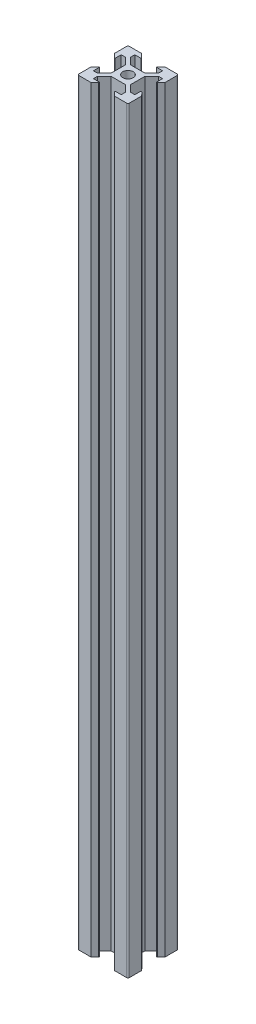
SolidWorks part; units mm, degrees
ref_plane "Front Plane" through (0, 0, 0) normal (0, 0, 1) x (1, 0, 0)
ref_plane "Top Plane" through (0, 0, 0) normal (0, 1, 0) x (1, 0, 0)
ref_plane "Right Plane" through (0, 0, 0) normal (1, 0, 0) x (0, 0, -1)
sketch "Sketch1" plane through (0, 0, 0) normal (0, 1, 0) x (1, 0, 0)
  line L0 (-2.1465, 12.2219) -> (22.938, 12.2219) construction
  line L1 (7.155, 13.9) -> (4.5, 16.555)
  line L2 (0.5, 0) -> (5.42, 0)
  line L3 (0, 0.5) -> (0, 5.42)
  line L4 (0.5, 20) -> (5.42, 20)
  line L5 (20, 0.5) -> (20, 19.5)
  line L6 (7.155, 13.9) -> (12.8341, 13.9)
  line L7 (6.1, 12.845) -> (6.1, 7.1491)
  line L8 (7.1445, 6.1) -> (12.8546, 6.1)
  line L9 (13.9, 12.8445) -> (13.9, 7.1491)
  line L10 (0, 20) -> (4.5, 20)
  line L11 (0, 20) -> (0, 15.5)
  line L12 (1.8, 15.5) -> (3.445, 15.5)
  line L13 (4.5, 18.2) -> (4.5, 16.555)
  line L14 (6.1, 12.845) -> (6.0943, 12.8393)
  line L15 (3.445, 15.5) -> (3.4393, 15.4943)
  line L16 (6.0943, 12.8393) -> (3.4393, 15.4943)
  line L17 (5.42, 20) -> (6.875, 18.545)
  line L18 (4.5, 20) -> (5.42, 20)
  line L19 (6.875, 20) -> (19.5, 20)
  line L20 (4.5, 18.2) -> (6.875, 18.2)
  line L21 (6.875, 20) -> (6.875, 18.2)
  line L22 (0, 14.58) -> (1.46, 13.12)
  line L23 (15.5, 18.2) -> (15.5, 16.555)
  line L24 (0, 15.5) -> (0, 13.12)
  line L25 (0, 13.12) -> (1.8, 13.12)
  line L26 (1.8, 15.5) -> (1.8, 13.12)
  line L27 (16.5507, 15.5) -> (18.2, 15.5)
  line L28 (15.5, 18.2) -> (13.12, 18.2)
  line L29 (13.12, 18.2) -> (13.12, 18.545)
  line L30 (13.12, 18.545) -> (14.575, 20)
  line L31 (18.2, 15.5) -> (18.2, 13.12)
  line L32 (18.2, 13.12) -> (18.5344, 13.12)
  line L33 (18.5344, 13.12) -> (20, 14.58)
  line L34 (12.8341, 13.9) -> (15.5, 16.555)
  line L35 (18.2, 4.5) -> (16.5585, 4.5)
  line L36 (16.5507, 15.5) -> (16.5585, 15.4922)
  line L37 (13.8926, 12.8372) -> (16.5585, 15.4922)
  line L38 (15.5, 3.4377) -> (15.5, 1.8)
  line L39 (18.2, 4.5) -> (18.2, 6.88)
  line L40 (18.2, 6.88) -> (18.6069, 6.88)
  line L41 (20, 5.42) -> (18.6069, 6.88)
  line L42 (15.5, 1.8) -> (13.12, 1.8)
  line L43 (13.12, 1.8) -> (13.12, 1.455)
  line L44 (14.575, 0) -> (13.12, 1.455)
  line L45 (13.9, 7.1491) -> (16.5585, 4.5)
  line L46 (12.8546, 6.1) -> (12.8412, 6.0865)
  line L47 (15.5, 3.4377) -> (15.4997, 3.4375)
  line L48 (12.8412, 6.0865) -> (15.4997, 3.4375)
  line L49 (1.8, 4.5) -> (3.4393, 4.5)
  line L50 (4.5, 3.4393) -> (4.5, 1.8)
  line L51 (1.46, 6.88) -> (1.8, 6.88)
  line L52 (1.8, 6.88) -> (1.8, 4.5)
  line L53 (0, 5.42) -> (1.46, 6.88)
  line L54 (4.5, 1.8) -> (6.875, 1.8)
  line L55 (6.875, 1.8) -> (6.875, 1.455)
  line L56 (5.42, 0) -> (6.875, 1.455)
  line L57 (3.4393, 4.5) -> (6.1, 7.1491)
  line L58 (14.575, 0) -> (19.5, 0)
  line L59 (7.1445, 6.1) -> (7.1583, 6.0861)
  line L60 (4.4977, 3.437) -> (7.1583, 6.0861)
  line L61 (0, 6.88) -> (0, 19.5)
  circle A0 centre (10, 10) radius 2.0746
  arc A1 (0.5, 0) -> (0, 0.5) centre (0.5, 0.5) cw
  arc A2 (19.5, 0) -> (20, 0.5) centre (19.5, 0.5) ccw
  arc A3 (19.5, 20) -> (20, 19.5) centre (19.5, 19.5) cw
  arc A4 (0, 19.5) -> (0.5, 20) centre (0.5, 19.5) cw
  point P22 (0, 0)
  point P25 (20, 0)
  dimension "D14" = 0.5
  dimension "D1" = 20
  dimension "D2" = 20
  dimension "D3" = 10
  dimension "D4" = 10
  dimension "D5" = 7.8
  dimension "D6" = 7.8
  dimension "D7" = 3.9
  dimension "D8" = 3.9
  dimension "D9" = 4.5
  dimension "D10" = 4.5
  dimension "D11" = 45
  dimension "D12" = 1.5
  dimension "D13" = 1.5
  dimension "D15" = 2.375
  dimension "D16" = 1.8
  dimension "D17" = 9.155
  dimension "D18" = 45
  dimension "D19" = 2.38
  dimension "D20" = 1.8
  dimension "D21" = 4.58
  dimension "D22" = 45
  dimension "D24" = 2.38
  dimension "D25" = 2.38
  dimension "D27" = 2.38
  dimension "D28" = 9.16
  dimension "D29" = 4.58
  dimension "D30" = 2.38
  dimension "D31" = 1.8
  dimension "D32" = 45
  dimension "D33" = 1.5
  dimension "D34" = 2.38
  dimension "D35" = 45
  dimension "D36" = 4.58
  dimension "D37" = 2.375
  dimension "D39" = 45
  dimension "D40" = 4.58
  dimension "D41" = 1.5
extrude "Boss-Extrude2" add sketch "Sketch1" along normal blind 300
